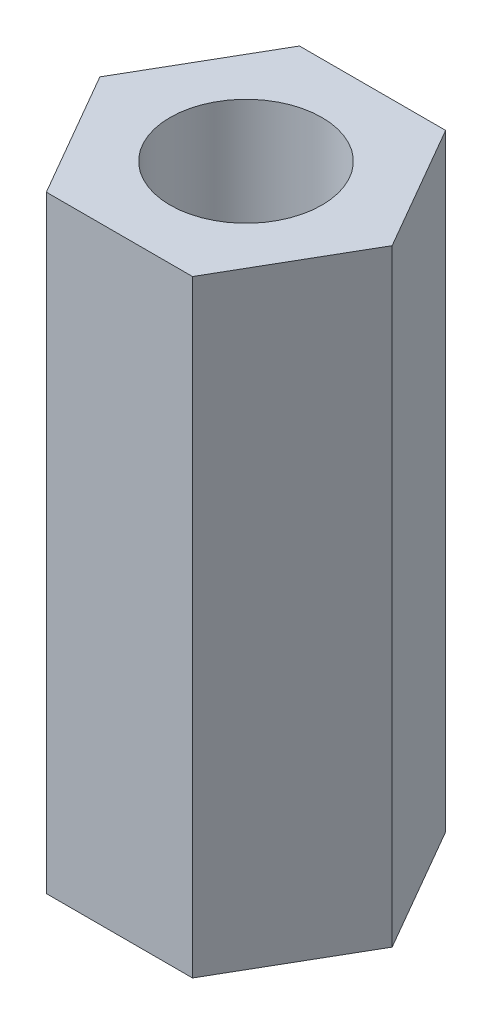
SolidWorks part; units mm, degrees
ref_plane "Front Plane" through (0, 0, 0) normal (0, 0, 1) x (1, 0, 0)
ref_plane "Top Plane" through (0, 0, 0) normal (0, 1, 0) x (1, 0, 0)
ref_plane "Right Plane" through (0, 0, 0) normal (1, 0, 0) x (0, 0, -1)
sketch "Sketch2" plane through (0, 0, 0) normal (0, 1, 0) x (1, 0, 0)
  line L0 (1.4435, 2.5002) -> (2.887, 0)
  line L1 (2.887, 0) -> (1.4435, -2.5002)
  line L2 (1.4435, -2.5002) -> (-1.4435, -2.5002)
  line L3 (-1.4435, -2.5002) -> (-2.887, 0)
  line L4 (-2.887, 0) -> (-1.4435, 2.5002)
  line L5 (-1.4435, 2.5002) -> (1.4435, 2.5002)
  circle A0 centre (0, 0) radius 1.5
  dimension "D1" = 2.887
  dimension "D2" = 2.887
extrude "Boss-Extrude1" add sketch "Sketch2" along normal blind 12
